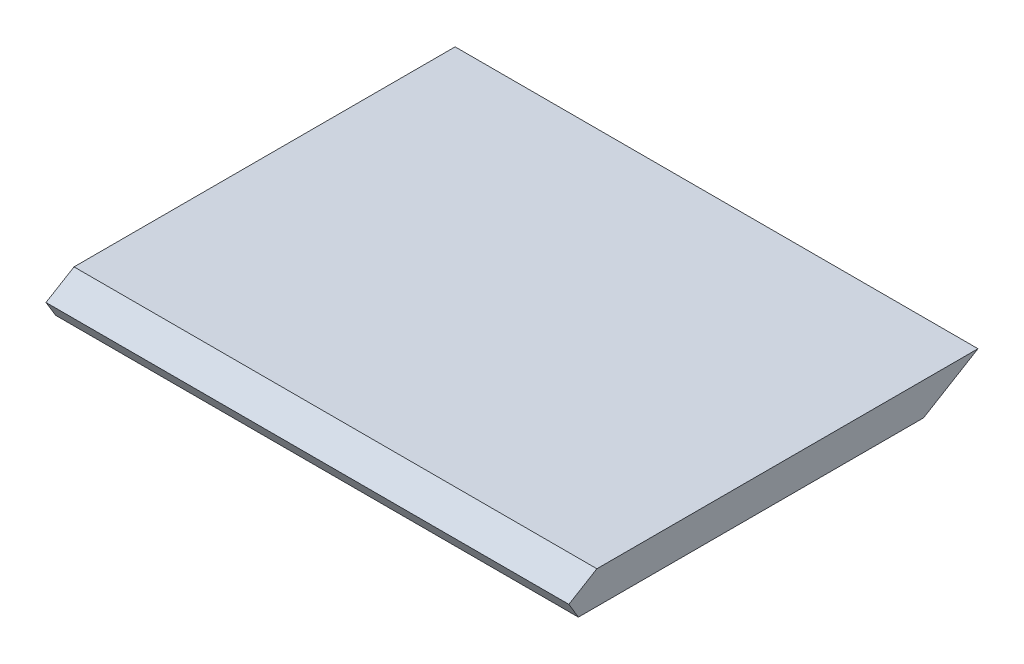
SolidWorks part; units mm, degrees
material "Balsa"
ref_plane "Front Plane" through (0, 0, 0) normal (0, 0, 1) x (1, 0, 0)
ref_plane "Top Plane" through (0, 0, 0) normal (0, 1, 0) x (1, 0, 0)
ref_plane "Right Plane" through (0, 0, 0) normal (1, 0, 0) x (0, 0, -1)
sketch "Sketch3" plane through (71.1933, 0, 0) normal (1, 0, 0) x (0, 0, -1)
  line L0 (56.968, 6.35) -> (46.3846, 0)
  line L1 (46.3846, 0) -> (-20.6804, 0)
  line L2 (-20.6804, 0) -> (-22.5302, 3.083)
  line L3 (-22.5302, 3.083) -> (-227.7008, 345.034) construction
  line L4 (56.968, 6.35) -> (63.7199, 10.4011) construction
  line L6 (-22.5302, 3.083) -> (-17.0851, 6.35)
  line L7 (-17.0851, 6.35) -> (56.968, 6.35)
extrude "Boss-Extrude2" add sketch "Sketch3" against normal up to surface (101.6 mm away)
